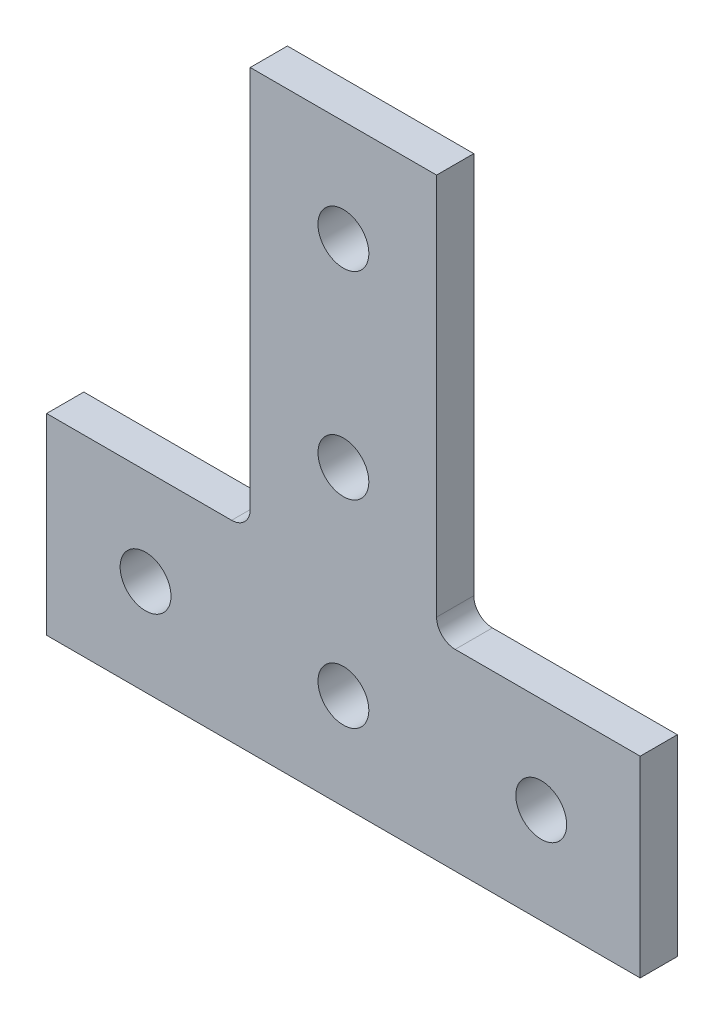
SolidWorks part; units mm, degrees
ref_plane "Front Plane" through (0, 0, 0) normal (0, 0, 1) x (1, 0, 0)
ref_plane "Top Plane" through (0, 0, 0) normal (0, 1, 0) x (1, 0, 0)
ref_plane "Right Plane" through (0, 0, 0) normal (1, 0, 0) x (0, 0, -1)
sketch "Sketch1" plane through (0, 0, 0) normal (0, 0, 1) x (1, 0, 0)
  line L0 (0, 38.1) -> (0, -38.1) construction
  line L1 (-38.1, -38.1) -> (38.1, -38.1) construction
  line L2 (38.1, -38.1) -> (38.1, -13.4366) construction
  line L3 (25.4, -22.5044) -> (25.4, -29.0322) construction
  line L4 (11.9634, 38.1) -> (-11.9634, 38.1) construction
  point P0 (0, -0.3683)
  point P4 (0, 0)
  point P8 (0, -38.1)
  point P11 (25.4, -25.7683)
  point P12 (38.1, -25.7683)
  point P15 (0, 38.1)
  dimension "Length" = 76.2
  dimension "Width1" = 24.6634
  dimension "Hole Dia" = 6.5278
  dimension "Hole to Edge" = 12.7
  dimension "Hole Spacing" = 25.4
  dimension "Width2" = 23.9268
sketch "Sketch2" plane through (0, 0, 0) normal (1, 0, 0) x (0, 0, -1)
  line L0 (2.3876, 0) -> (-2.3876, 0) construction
  point P4 (0, 0)
  dimension "Thickness" = 4.7752
sketch "Sketch3" plane through (0, 0, 0) normal (0, 0, 1) x (1, 0, 0)
  line L0 (38.1, -38.1) -> (-38.1, -38.1)
  line L1 (38.1, -38.1) -> (38.1, -13.4366)
  line L2 (38.1, -13.4366) -> (14.351, -13.4366)
  line L3 (11.9634, -11.049) -> (11.9634, 38.1)
  line L4 (11.9634, 38.1) -> (-11.9634, 38.1)
  line L5 (11.9634, 38.1) -> (-11.9634, 38.1) construction
  line L6 (-38.1, -38.1) -> (38.1, -38.1) construction
  line L7 (0, -38.1) -> (0, 38.1) construction
  line L8 (-11.9634, -11.049) -> (-11.9634, 38.1)
  line L9 (-38.1, -13.4366) -> (-14.351, -13.4366)
  line L10 (-38.1, -38.1) -> (-38.1, -13.4366)
  arc A0 (-11.9634, -11.049) -> (-14.351, -13.4366) centre (-14.351, -11.049) cw
  arc A1 (14.351, -13.4366) -> (11.9634, -11.049) centre (14.351, -11.049) cw
  point P20 (-11.9634, -13.4366)
  point P23 (11.9634, -13.4366)
  dimension "Radius" = 2.3876
extrude "Boss-Extrude1" add sketch "Sketch3" against normal up to vertex (2.3876 mm away) and the other way up to vertex (2.3876 mm away) up to point (0, 0, -2.3876) other way up to point (0, 0, 2.3876)
sketch "Sketch4" plane through (0, 0, 2.3876) normal (0, 0, 1) x (1, 0, 0)
  line L0 (25.4, -22.5044) -> (25.4, -29.0322) construction
  line L1 (0, 38.1) -> (0, -38.1) construction
  line L2 (0, -38.1) -> (0, 38.1) construction
  line L3 (-38.1, -38.1) -> (38.1, -38.1) construction
  line L4 (0, -0.3683) -> (-11.9634, -0.3683) construction
  line L5 (-11.9634, 38.1) -> (-11.9634, -11.049) construction
  circle A0 centre (25.4, -25.7683) radius 3.2639
  circle A1 centre (0, -25.7683) radius 3.2639
  circle A2 centre (-25.4, -25.7683) radius 3.2639
  circle A3 centre (0, -0.3683) radius 3.2639
  circle A4 centre (0, 25.0317) radius 3.2639
extrude "Cut-Extrude1" cut sketch "Sketch4" against normal through all
